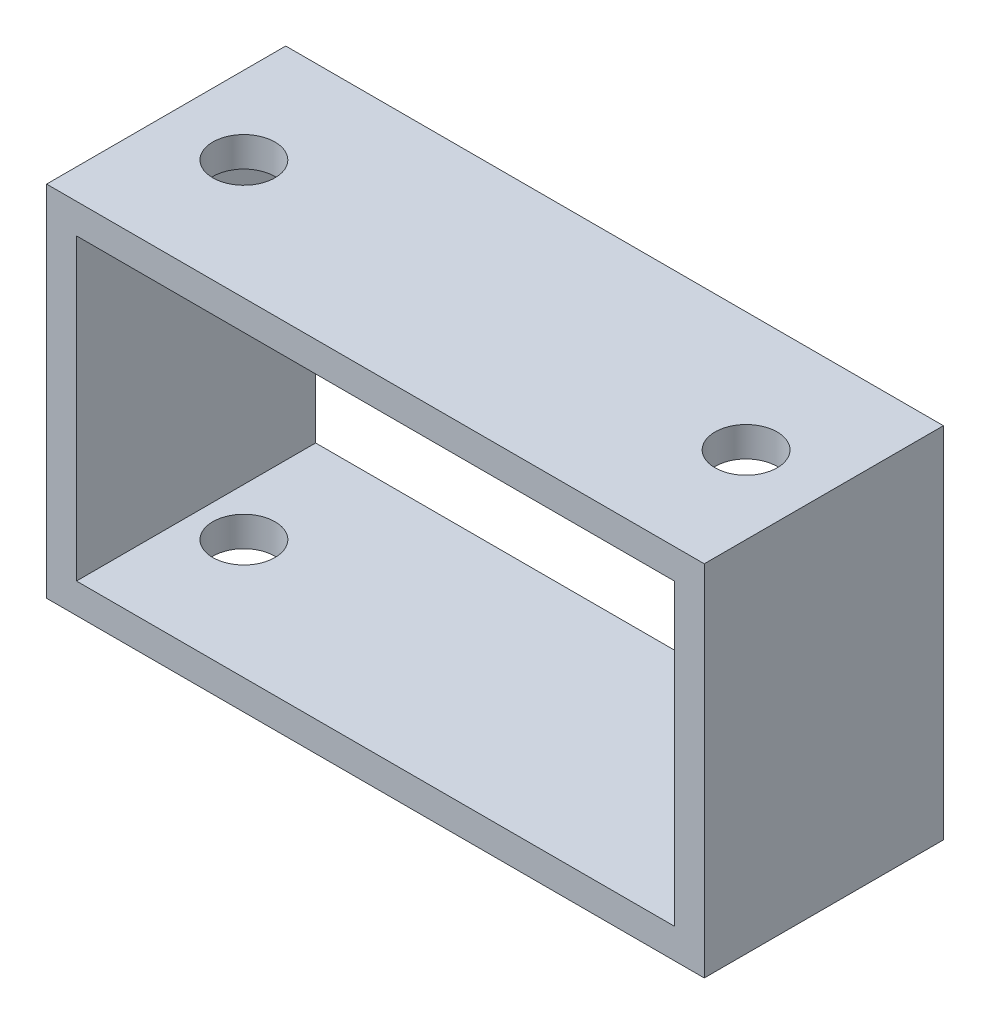
SolidWorks part; units mm, degrees
ref_plane "前视基准面" through (0, 0, 0) normal (0, 0, 1) x (1, 0, 0)
ref_plane "上视基准面" through (0, 0, 0) normal (0, 1, 0) x (1, 0, 0)
ref_plane "右视基准面" through (0, 0, 0) normal (1, 0, 0) x (0, 0, -1)
sketch "草图1" plane through (0, 0, 0) normal (0, 1, 0) x (1, 0, 0)
  line L0 (-27.5, 0) -> (27.5, 0) construction
  line L1 (-27.5, -10) -> (27.5, -10)
  line L2 (-27.5, -10) -> (-27.5, 10)
  line L3 (-27.5, 10) -> (27.5, 10)
  line L4 (27.5, -10) -> (27.5, 10)
  line L5 (-27.5, -10) -> (27.5, 10) construction
  line L6 (-27.5, 10) -> (27.5, -10) construction
  point P0 (0, 0)
  dimension "D1" = 20
  dimension "D2" = 55
extrude "凸台-拉伸1" add sketch "草图1" along normal blind 30
sketch "草图2" plane through (0, 0, 10) normal (0, 0, 1) x (1, 0, 0)
  line L0 (-27.5, 15) -> (27.5, 15) construction
  line L1 (-25, 2.5) -> (25, 2.5)
  line L2 (-25, 2.5) -> (-25, 27.5)
  line L3 (-25, 27.5) -> (25, 27.5)
  line L4 (25, 2.5) -> (25, 27.5)
  line L5 (-25, 2.5) -> (25, 27.5) construction
  line L6 (-25, 27.5) -> (25, 2.5) construction
  line L7 (-27.5, 30) -> (-27.5, 0) construction
  line L8 (27.5, 30) -> (27.5, 0) construction
  line L9 (0, 30) -> (0, 0) construction
  line L10 (-27.5, 30) -> (27.5, 30) construction
  point P0 (0, 15)
  dimension "D1" = 50
  dimension "D2" = 25
extrude "切除-拉伸1" cut sketch "草图2" against normal up to next
sketch "草图3" plane through (0, 30, 0) normal (0, 1, 0) x (1, 0, 0)
  line L0 (-27.5, 0) -> (27.5, 0) construction
  line L1 (-27.5, 10) -> (-27.5, -10) construction
  line L2 (27.5, -10) -> (27.5, 10) construction
  circle A0 centre (-21, 0) radius 2.6
  circle A1 centre (21, 0) radius 2.6
  dimension "D3" = 5.2
  dimension "D4" = 5.2
  dimension "D1" = 6.5
  dimension "D2" = 6.5
extrude "切除-拉伸2" cut sketch "草图3" against normal up to surface (30 mm away) up to face at (0, 0, 0)
